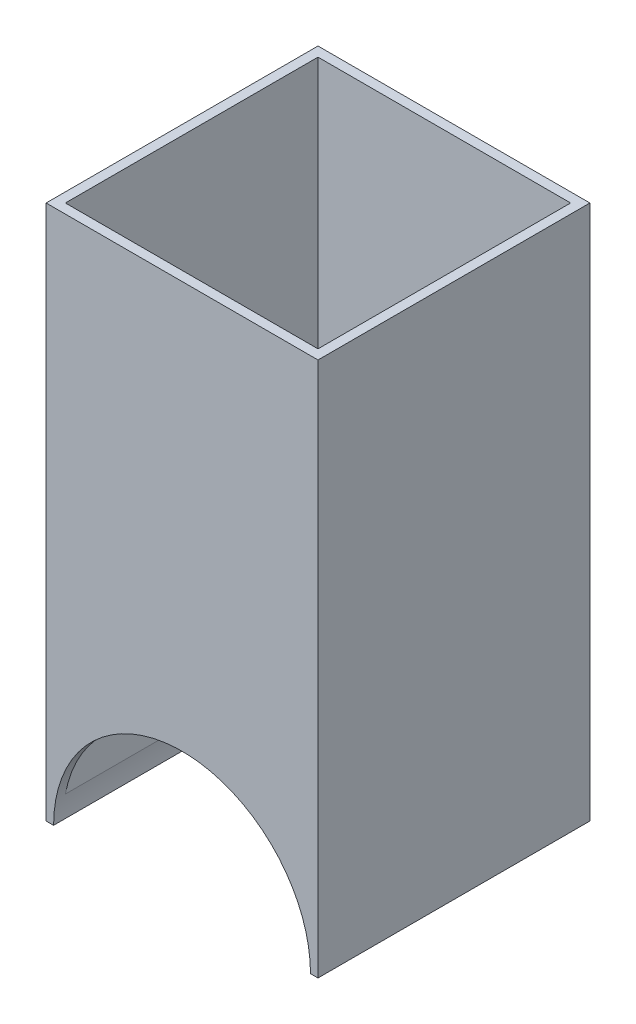
SolidWorks part; units mm, degrees
ref_plane "Front Plane" through (0, 0, 0) normal (0, 0, 1) x (1, 0, 0)
ref_plane "Top Plane" through (0, 0, 0) normal (0, 1, 0) x (1, 0, 0)
ref_plane "Right Plane" through (0, 0, 0) normal (1, 0, 0) x (0, 0, -1)
sketch "Sketch1" plane through (0, 0, 0) normal (0, 1, 0) x (1, 0, 0)
  line L0 (-11.8, 11.8) -> (-11.8, -11.8)
  line L1 (-12.7, 12.7) -> (12.7, 12.7)
  line L2 (-12.7, 12.7) -> (-12.7, -12.7)
  line L3 (-12.7, -12.7) -> (12.7, -12.7)
  line L4 (12.7, 12.7) -> (12.7, -12.7)
  line L5 (-12.7, 12.7) -> (12.7, -12.7) construction
  line L6 (-12.7, -12.7) -> (12.7, 12.7) construction
  line L7 (-11.8, -11.8) -> (11.8, -11.8)
  line L8 (11.8, 11.8) -> (11.8, -11.8)
  line L9 (-11.8, 11.8) -> (11.8, 11.8)
  point P0 (0, 0)
  dimension "D1" = 0.9
extrude "Boss-Extrude1" add sketch "Sketch1" along normal blind 50
sketch "Sketch2" plane through (0, 0, 12.7) normal (0, 0, 1) x (1, 0, 0)
  line L0 (-12, 0) -> (12, 0)
  arc A0 (12, 0) -> (-12, 0) centre (0, 0) ccw
extrude "Cut-Extrude1" cut sketch "Sketch2" against normal blind 25.4
